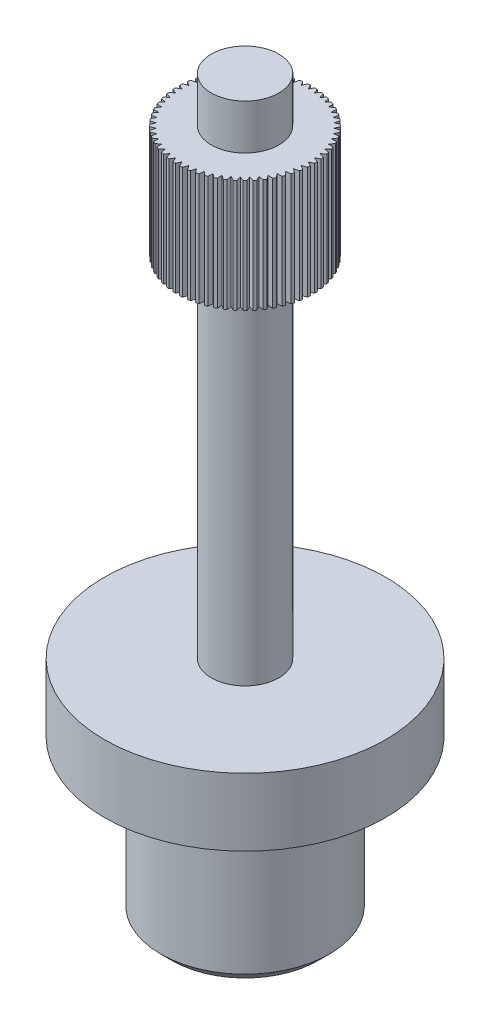
SolidWorks part; units mm, degrees
ref_plane "前视" through (0, 0, 0) normal (0, 0, 1) x (1, 0, 0)
ref_plane "上视" through (0, 0, 0) normal (0, 1, 0) x (1, 0, 0)
ref_plane "右视" through (0, 0, 0) normal (1, 0, 0) x (0, 0, -1)
sketch "草图1" plane through (0, 0, 0) normal (0, 1, 0) x (1, 0, 0)
  circle A0 centre (0, 0) radius 7.5
  dimension "D1" = 15
extrude "凸台-拉伸1" add sketch "草图1" along normal blind 14
sketch "草图2" plane through (0, 14, 0) normal (0, 1, 0) x (1, 0, 0)
  circle A0 centre (0, 0) radius 12.5
  dimension "D1" = 25
extrude "凸台-拉伸2" add sketch "草图2" along normal blind 6
chamfer "倒角1" distance 1 angle 45 1 edges at (0, 0, 7.5)
sketch "草图5" plane through (0, 20, 0) normal (0, 1, 0) x (1, 0, 0)
  circle A0 centre (0, 0) radius 3
  dimension "D1" = 6
extrude "凸台-拉伸3" add sketch "草图5" along normal blind 45
sketch "草图6" plane through (0, 20, 0) normal (0, 1, 0) x (1, 0, 0)
  circle A0 centre (0, 0) radius 6
  dimension "D1" = 12
extrude "凸台-拉伸4" add sketch "草图6" along normal blind 10 from offset 31
sketch "草图7" plane through (0, 61, 0) normal (0, 1, 0) x (1, 0, 0)
  line L0 (0, 0) -> (0, 6) construction
  line L1 (0, 5.6) -> (-0.1927, 5.9969)
  line L2 (0, 5.6) -> (0.1927, 5.9969)
  circle A0 centre (0, 0) radius 6 construction
  arc A1 (0.1927, 5.9969) -> (-0.1927, 5.9969) centre (0, 0) ccw
extrude "切除-拉伸2" cut sketch "草图7" against normal blind 10
pattern_circular "阵列(圆周)2" count 60 over 360 about axis through (0, 0, 0) along (0, 1, 0) of "切除-拉伸2"
